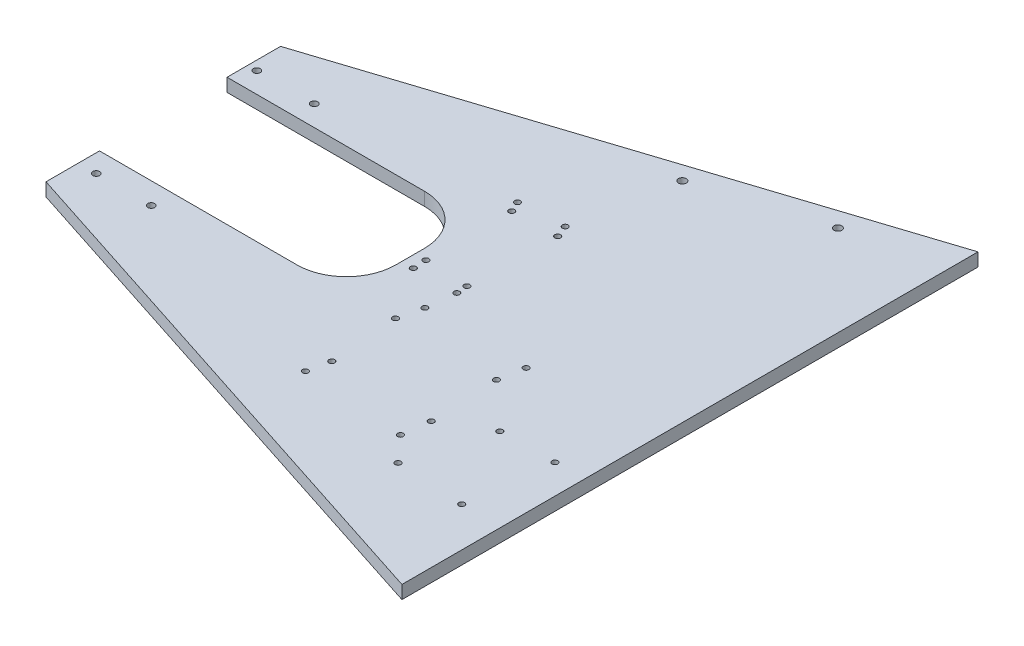
SolidWorks part; units mm, degrees
ref_plane "Front Plane" through (0, 0, 0) normal (0, 0, 1) x (1, 0, 0)
ref_plane "Top Plane" through (0, 0, 0) normal (0, 1, 0) x (1, 0, 0)
ref_plane "Right Plane" through (0, 0, 0) normal (1, 0, 0) x (0, 0, -1)
sketch "Sketch2" plane through (0, 0, 0) normal (0, 1, 0) x (1, 0, 0)
  line L0 (-320, 142.5) -> (320, 350)
  line L1 (320, 350) -> (320, -350)
  line L2 (320, -350) -> (-320, -142.5)
  line L3 (-320, -142.5) -> (-320, -77.5)
  line L4 (-320, -77.5) -> (-20, -77.5)
  line L5 (-20, -77.5) -> (-20, 77.5)
  line L6 (-20, 77.5) -> (-320, 77.5)
  line L7 (-320, 77.5) -> (-320, 142.5)
  line L8 (0, 0) -> (320, 0) construction
  line L9 (0, 0) -> (-20, 0) construction
  point P2 (0, 0)
  point P3 (-319.7061, 142.5)
  dimension "D1" = 700
  dimension "D2" = 640
  dimension "D3" = 65
  dimension "D4" = 155
  dimension "D5" = 300
  dimension "D6" = 320
extrude "Boss-Extrude1" add sketch "Sketch2" against normal blind 16
fillet "Fillet1" radius 60 2 edges at (-20, -8, 77.5) (-20, -8, -77.5)
sketch "Sketch3" plane through (0, 0, 0) normal (0, 1, 0) x (1, 0, 0)
  line L0 (524.6162, 0) -> (22.916, 0) construction
  circle A27 centre (45.5731, 3.3586) radius 3.5
  circle A28 centre (-231.0932, -103.5561) radius 4.25
  circle A29 centre (-298.1799, -103.306) radius 4.25
  circle A30 centre (42.5662, -157.7591) radius 3.5
  circle A31 centre (36.9309, -184.2346) radius 3.5
  circle A32 centre (271.8939, -229.2237) radius 3.5
  circle A33 centre (189.7823, -224.481) radius 3.5
  circle A34 centre (161.7032, -193.5714) radius 3.5
  circle A35 centre (165.9596, -160.3918) radius 3.5
  circle A36 centre (218.3345, -129.3929) radius 3.5
  circle A37 centre (284.4795, -128.6264) radius 3.5
  circle A38 centre (167.6183, -46.6966) radius 3.5
  circle A39 centre (162.0996, -77.2337) radius 3.5
  circle A40 centre (36.0886, -73.9158) radius 3.5
  circle A41 centre (42.8755, -45.0543) radius 3.5
  circle A42 centre (46.5852, -9.907) radius 3.5
  circle A43 centre (-5.9115, -10.2555) radius 3.5
  circle A44 centre (65.685, 245.1109) radius 4.75
  circle A45 centre (209.8193, 289.933) radius 4.75
  circle A46 centre (-239.1242, 102.5486) radius 4.25
  circle A47 centre (-308.8881, 102.5486) radius 4.25
  circle A48 centre (42.5662, 125.8149) radius 3.5
  circle A49 centre (-11.9089, 122.3506) radius 3.5
  circle A50 centre (48.2866, 110.9845) radius 3.5
  circle A51 centre (-6.149, 109.5508) radius 3.5
  circle A52 centre (-6.6976, 5.8355) radius 3.5
  dimension "D1" = 9.5
extrude "Cut-Extrude1" cut sketch "Sketch3" against normal through all
